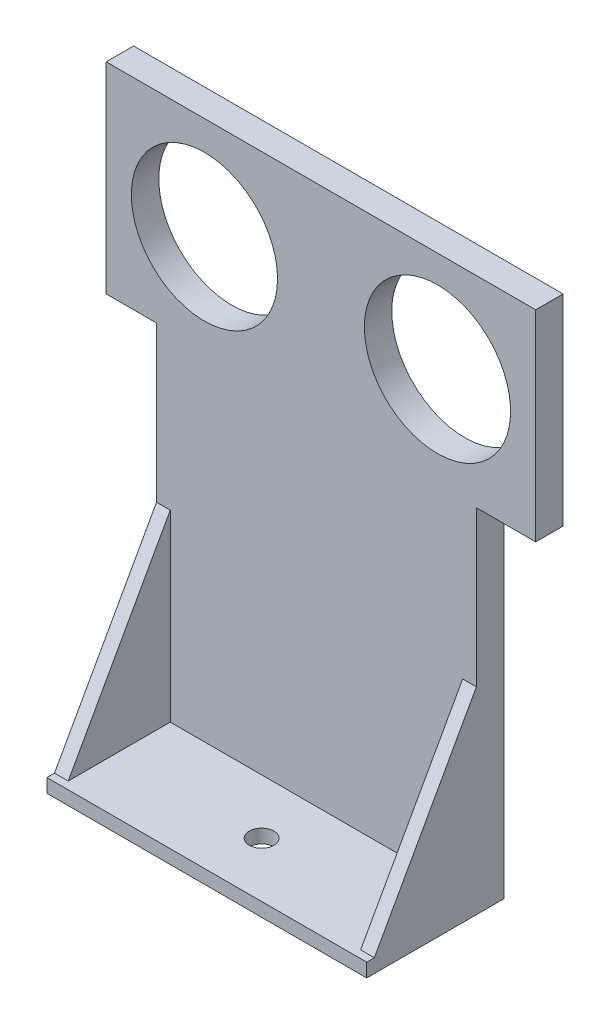
SolidWorks part; units mm, degrees
ref_plane "Front Plane" through (0, 0, 0) normal (0, 0, 1) x (1, 0, 0)
ref_plane "Top Plane" through (0, 0, 0) normal (0, 1, 0) x (1, 0, 0)
ref_plane "Right Plane" through (0, 0, 0) normal (1, 0, 0) x (0, 0, -1)
sketch "Sketch2" plane through (0, 0, 0) normal (0, 1, 0) x (1, 0, 0)
  line L0 (0, 0) -> (0, -6)
  line L1 (17.5, -6) -> (-17.5, -6)
  line L2 (17.5, -6) -> (17.5, 6)
  line L3 (17.5, 6) -> (-17.5, 6)
  line L4 (-17.5, -6) -> (-17.5, 6)
  line L5 (17.5, -6) -> (-17.5, 6) construction
  line L6 (17.5, 6) -> (-17.5, -6) construction
  circle A0 centre (0, 0) radius 1.35
  point P0 (0, 0)
  dimension "D3" = 2.7
  dimension "D1" = 35
  dimension "D2" = 12
ref_plane "Plane1" through (0, 0, -6) normal (0, 0, -1) x (-1, 0, 0)
sketch "Sketch3" plane through (0, 0, -6) normal (0, 0, -1) x (-1, 0, 0)
  line L0 (-17.5, 0) -> (17.5, 0) construction
  line L1 (17.5, 0) -> (-17.5, 0)
  line L2 (17.5, 0) -> (17.5, 38.5737)
  line L3 (17.5, 38.5737) -> (23.0098, 38.5737)
  line L4 (-17.5, 0) -> (-17.5, 38.5737)
  line L5 (-17.5, 0) -> (17.5, 0) construction
  line L7 (-23.9902, 38.5737) -> (-17.5, 38.5737)
  line L8 (-23.9902, 38.5737) -> (-23.9902, 60.5737)
  line L9 (-23.9902, 60.5737) -> (23.0098, 60.5737)
  line L10 (23.0098, 38.5737) -> (23.0098, 60.5737)
  line L11 (-23.9902, 38.5737) -> (23.0098, 60.5737) construction
  line L12 (-23.9902, 60.5737) -> (23.0098, 38.5737) construction
  circle A0 centre (-13.2402, 49.5737) radius 8
  circle A1 centre (12.2598, 49.3746) radius 8
  point P8 (-0.4902, 49.5737)
  point P10 (-0.4133, 59.9997)
  dimension "D1" = 16
  dimension "D5" = 25.5
  dimension "D6" = 16
  dimension "D2" = 22
  dimension "D3" = 47
  dimension "D4" = 10.75
ref_plane "Plane2" through (17.5, 0, 0) normal (1, 0, 0) x (0, 0, -1)
sketch "Sketch4" plane through (17.5, 0, 0) normal (1, 0, 0) x (0, 0, -1)
  line L0 (6, 21.5925) -> (-6, 0)
  line L1 (-6, 0) -> (6, 0)
  line L4 (6, 0) -> (6, 21.5925)
ref_plane "Plane3" through (-17.5, 0, 0) normal (-1, 0, 0) x (0, 1, 0)
sketch "Sketch5" plane through (-17.5, 0, 0) normal (-1, 0, 0) x (0, 1, 0)
  line L0 (21.59, 6) -> (0, -6)
  line L2 (0, -6) -> (0, 6)
  line L3 (0, 6) -> (21.59, 6)
  dimension "D1" = 21.59
extrude "Boss-Extrude3" add sketch "Sketch5" against normal blind 1.5
extrude "Boss-Extrude4" add sketch "Sketch4" against normal blind 1.5 separate body contours L0 L1 L4
extrude "Boss-Extrude7" add sketch "Sketch2" along normal blind 1.5 contours A0 | L3 L4 L1 L2
extrude "Boss-Extrude8" add sketch "Sketch3" along normal blind 3 contours L9 L10 L3 L2 L1 L4 L7 L8 | A1 | A0
